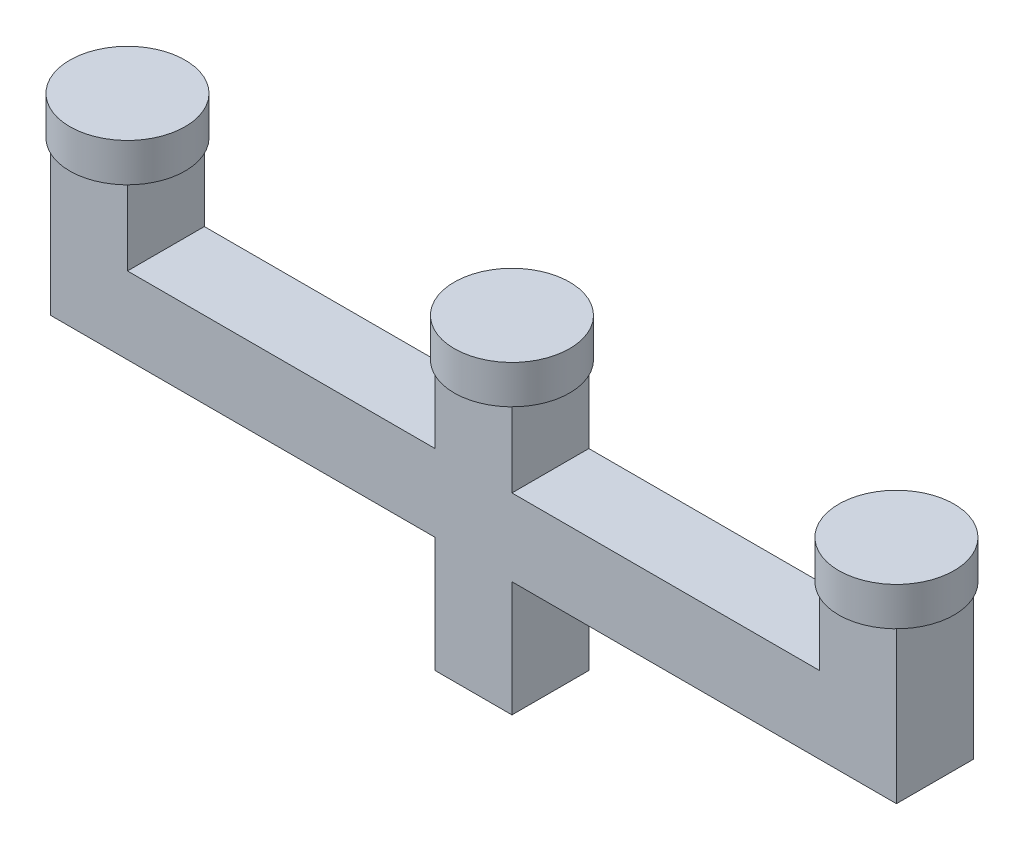
SolidWorks part; units mm, degrees
ref_plane "Front" through (0, 0, 0) normal (0, 0, 1) x (1, 0, 0)
ref_plane "Top" through (0, 0, 0) normal (0, 1, 0) x (1, 0, 0)
ref_plane "Right" through (0, 0, 0) normal (1, 0, 0) x (0, 0, -1)
sketch "Esquisse1" plane through (0, 0, 0) normal (0, 0, 1) x (1, 0, 0)
  line L0 (110, 0) -> (-110, 0)
  line L1 (-110, 0) -> (-110, 40)
  line L2 (-110, 40) -> (-90, 40)
  line L3 (-90, 40) -> (-90, 20)
  line L4 (-90, 20) -> (-10, 20)
  line L5 (-10, 20) -> (-10, 40)
  line L6 (-10, 40) -> (10, 40)
  line L7 (0, 40) -> (0, 0) construction
  line L8 (10, 20) -> (10, 40)
  line L9 (90, 20) -> (10, 20)
  line L10 (90, 40) -> (90, 20)
  line L11 (110, 40) -> (90, 40)
  line L12 (110, 0) -> (110, 40)
  dimension "D1" = 20
  dimension "D2" = 100
  dimension "D3" = 40
  dimension "D4" = 20
  dimension "D5" = 20
extrude "Boss.-Extru.1" add sketch "Esquisse1" along normal blind 20
sketch "Esquisse2" plane through (0, 0, 20) normal (0, 0, 1) x (1, 0, 0)
  line L0 (-110, 0) -> (110, 0) construction
  line L1 (-10, 0) -> (10, 0)
  line L2 (-10, 0) -> (-10, -30)
  line L3 (-10, -30) -> (10, -30)
  line L4 (10, 0) -> (10, -30)
  line L5 (0, -30) -> (0, 40) construction
  line L6 (10, 40) -> (-10, 40) construction
  dimension "D1" = 20
  dimension "D2" = 30
extrude "Boss.-Extru.2" add sketch "Esquisse2" against normal up to vertex (20 mm away)
sketch "Esquisse3" plane through (0, 40, 0) normal (0, 1, 0) x (1, 0, 0)
  line L0 (0, -20) -> (0, 0) construction
  line L1 (10, -20) -> (-10, -20) construction
  line L2 (-100, -20) -> (-100, 0) construction
  line L3 (-90, -20) -> (-110, -20) construction
  line L4 (-90, 0) -> (-110, 0) construction
  line L5 (100, -20) -> (100, 0) construction
  line L6 (110, -20) -> (90, -20) construction
  line L7 (110, 0) -> (90, 0) construction
  circle A0 centre (0, -10) radius 15
  circle A1 centre (-100, -10) radius 15
  circle A2 centre (100, -10) radius 15
  dimension "D1" = 30
extrude "Boss.-Extru.3" add sketch "Esquisse3" along normal blind 10
